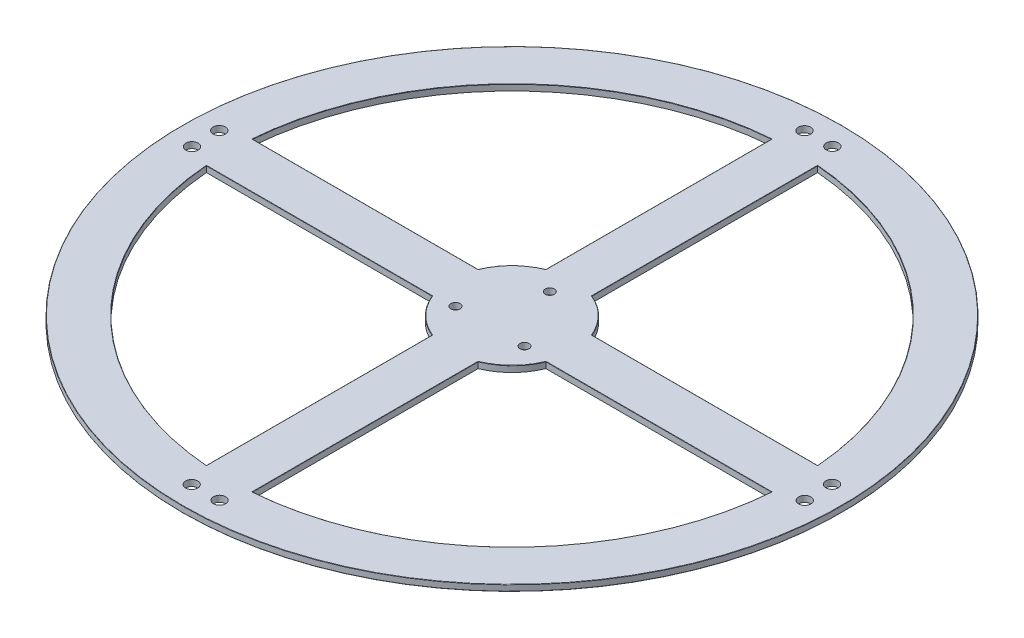
SolidWorks part; units mm, degrees
material "Plain Carbon Steel"
ref_plane "Front Plane" through (0, 0, 0) normal (0, 0, 1) x (1, 0, 0)
ref_plane "Top Plane" through (0, 0, 0) normal (0, 1, 0) x (1, 0, 0)
ref_plane "Right Plane" through (0, 0, 0) normal (1, 0, 0) x (0, 0, -1)
sketch "Sketch1" plane through (0, 0, 0) normal (0, 1, 0) x (1, 0, 0)
  line L2 (-92.5, -7.5) -> (-18.5405, -7.5)
  line L3 (-7.5, 92.5) -> (-7.5, 18.5405)
  line L4 (-92.5, 7.5) -> (-18.5405, 7.5)
  line L5 (7.5, 92.5) -> (7.5, 18.5405)
  line L7 (-7.5, -18.5405) -> (-7.5, -92.5)
  line L12 (7.5, -18.5405) -> (7.5, -92.5)
  line L14 (18.5405, 7.5) -> (92.5, 7.5)
  line L16 (18.5405, -7.5) -> (92.5, -7.5)
  circle A0 centre (0, 0) radius 107.5
  arc A1 (-92.1954, -7.5) -> (-7.5, -92.1954) centre (0, 0) ccw
  arc A2 (-18.5405, -7.5) -> (-7.5, -18.5405) centre (0, 0) ccw
  arc A3 (18.5405, 7.5) -> (7.5, 18.5405) centre (0, 0) ccw
  arc A4 (-7.5, 18.5405) -> (-18.5405, 7.5) centre (0, 0) ccw
  arc A5 (7.5, -18.5405) -> (18.5405, -7.5) centre (0, 0) ccw
  arc A6 (7.5, -92.1954) -> (92.1954, -7.5) centre (0, 0) ccw
  arc A7 (92.1954, 7.5) -> (7.5, 92.1954) centre (0, 0) ccw
  arc A8 (-7.5, 92.1954) -> (-92.1954, 7.5) centre (0, 0) ccw
  circle A9 centre (-100, 4.5) radius 2
  circle A10 centre (-99.8987, -4.5) radius 2
  circle A11 centre (4.5, 100) radius 2
  circle A12 centre (-4.5, 99.8987) radius 2
  circle A13 centre (100, -4.5) radius 2
  circle A14 centre (99.8987, 4.5) radius 2
  circle A15 centre (-4.5, -100) radius 2
  circle A16 centre (4.5, -99.8987) radius 2
  point P46 (0, 0)
  dimension "D1" = 215
  dimension "D2" = 15
  dimension "D3" = 40
  dimension "D6" = 4
  dimension "D7" = 4
  dimension "D4" = 15
  dimension "D5" = 15
  dimension "D8" = 100
  dimension "D9" = 100
  dimension "D10" = 3
  dimension "D12" = 3
  dimension "D11" = 4
extrude "Boss-Extrude1" add sketch "Sketch1" along normal blind 2
sketch "Sketch2" plane through (0, 0, 0) normal (0, -1, 0) x (1, 0, 0)
  circle A0 centre (-11.8206, 6.6119) radius 1.5 construction
  circle A1 centre (-0.5623, -12.8881) radius 1.5 construction
  circle A2 centre (10.696, 6.6119) radius 1.5 construction
  circle A3 centre (-11.8206, 6.6119) radius 1.5
  circle A4 centre (-0.5623, -12.8881) radius 1.5
  circle A5 centre (10.696, 6.6119) radius 1.5
extrude "Cut-Extrude1" cut sketch "Sketch2" against normal through all
fillet "Fillet1" radius 0.1 18 edges at (0, 0, 107.5) (55.368, 2, 7.5) (14.1421, 2, 14.1421) (7.5, 2, 55.368) (65.4074, 2, 65.4074) (14.1421, 2, -14.1421) (55.368, 2, -7.5) (65.4074, 2, -65.4074) (7.5, 2, -55.368) (-55.368, 2, -7.5) (-14.1421, 2, -14.1421) (-7.5, 2, -55.368) (-65.4074, 2, -65.4074) (-7.5, 2, 55.368) (-14.1421, 2, 14.1421) (-55.368, 2, 7.5) (-65.4074, 2, 65.4074) (0, 2, 107.5)
